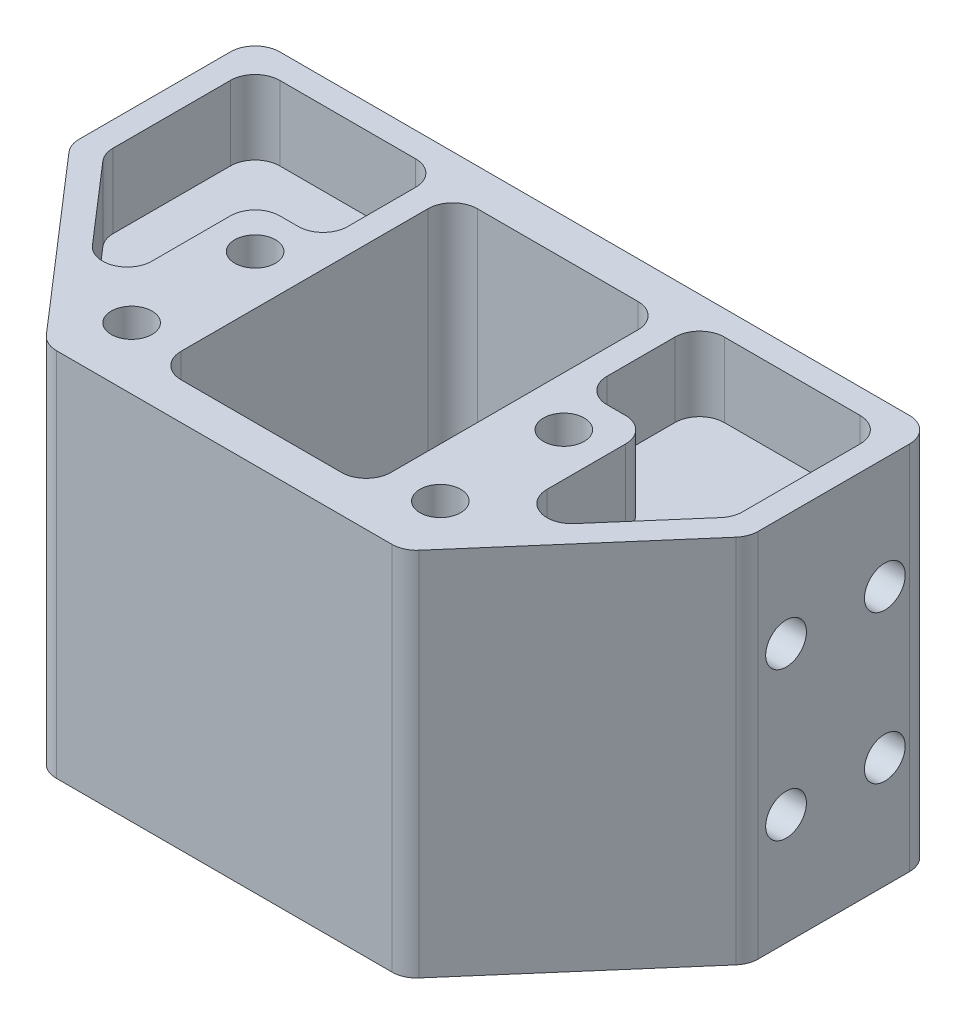
SolidWorks part; units mm, degrees
material "6061 合金"
ref_plane "前视基准面" through (0, 0, 0) normal (0, 0, 1) x (1, 0, 0)
ref_plane "上视基准面" through (0, 0, 0) normal (0, 1, 0) x (1, 0, 0)
ref_plane "右视基准面" through (0, 0, 0) normal (1, 0, 0) x (0, 0, -1)
other "Configuration Table"
sketch "草图1" plane through (0, 0, 0) normal (0, 0, 1) x (1, 0, 0)
  line L1 (-27.5, 15) -> (27.5, 15)
  line L2 (-27.5, 15) -> (-27.5, -15)
  line L3 (-27.5, -15) -> (27.5, -15)
  line L4 (27.5, 15) -> (27.5, -15)
  line L5 (-27.5, 15) -> (27.5, -15) construction
  line L6 (-27.5, -15) -> (27.5, 15) construction
  point P0 (0, 0)
  dimension "D1" = 55
  dimension "D2" = 30
extrude "凸台-拉伸1" add sketch "草图1" along normal blind 30
sketch "草图2" plane through (0, 15, 0) normal (0, 1, 0) x (1, 0, 0)
  line L0 (27.5, -30) -> (-27.5, -30) construction
  line L1 (-8.5, -3) -> (8.5, -3)
  line L2 (-8.5, -3) -> (-8.5, -27)
  line L3 (-8.5, -27) -> (8.5, -27)
  line L4 (8.5, -3) -> (8.5, -27)
  line L5 (-8.5, -3) -> (8.5, -27) construction
  line L6 (-8.5, -27) -> (8.5, -3) construction
  line L7 (27.5, 0) -> (-27.5, 0) construction
  line L9 (-12.5, -15) -> (12.5, -15) construction
  line L10 (-12.5, -15) -> (-12.5, -25) construction
  line L11 (-12.5, -25) -> (12.5, -25) construction
  line L12 (12.5, -15) -> (12.5, -25) construction
  line L13 (-12.5, -15) -> (12.5, -25) construction
  line L14 (-12.5, -25) -> (12.5, -15) construction
  circle A0 centre (12.5, -25) radius 1.65
  circle A1 centre (-12.5, -25) radius 1.65
  circle A2 centre (-12.5, -15) radius 1.65
  circle A3 centre (12.5, -15) radius 1.65
  point P0 (0, -15)
  point P10 (0, -20)
  dimension "D9" = 3.3
  dimension "D1" = 17
  dimension "D2" = 3
  dimension "D3" = 3
  dimension "D4" = 5
  dimension "D7" = 25
  dimension "D8" = 10
  dimension "D5" = 2
  dimension "D6" = 2
extrude "切除-拉伸1" cut sketch "草图2" against normal blind 40
sketch "草图7" plane through (0, 15, 0) normal (0, 1, 0) x (1, 0, 0)
  line L0 (27.5, -15) -> (27.5, -30)
  line L1 (27.5, -30) -> (27.5, 0) construction
  line L2 (27.5, -30) -> (14.5, -30)
  line L3 (27.5, -30) -> (-27.5, -30) construction
  line L4 (14.5, -30) -> (27.5, -15)
  line L5 (-14.5, -30) -> (-27.5, -30)
  line L6 (-27.5, -30) -> (-27.5, -15)
  line L7 (-27.5, -30) -> (-27.5, 0) construction
  line L8 (-27.5, -15) -> (-14.5, -30)
  dimension "D1" = 13
  dimension "D2" = 15
  dimension "D3" = 13
extrude "切除-拉伸3" cut sketch "草图7" against normal blind 40
sketch "草图8" plane through (0, 15, 0) normal (0, 1, 0) x (1, 0, 0)
  line L6 (-16, -25.2155) -> (-16, -11.5)
  line L7 (-16, -11.5) -> (-10.5, -11.5)
  line L8 (-10.5, -11.5) -> (-10.5, -2)
  line L9 (16, -25.2155) -> (16, -11.5)
  line L10 (16, -11.5) -> (10.5, -11.5)
  line L11 (10.5, -11.5) -> (10.5, -2)
  line L12 (-13.5867, -28) -> (13.5867, -28)
  line L13 (13.5867, -28) -> (25.5, -14.2539)
  line L14 (25.5, -14.2539) -> (25.5, -2)
  line L15 (25.5, -2) -> (-25.5, -2)
  line L16 (-25.5, -2) -> (-25.5, -14.2539)
  line L17 (-25.5, -14.2539) -> (-13.5867, -28)
  line L19 (16, -25.2155) -> (25.5, -14.2539)
  line L20 (25.5, -14.2539) -> (25.5, -2)
  line L21 (25.5, -2) -> (10.5, -2)
  line L22 (-25.5, -2) -> (-25.5, -14.2539)
  line L23 (-25.5, -14.2539) -> (-16, -25.2155)
  line L24 (-10.5, -2) -> (-25.5, -2)
  line L25 (-8.5, -3) -> (-8.5, -27) construction
  line L26 (8.5, -27) -> (8.5, -3) construction
  circle A0 centre (-12.5, -15) radius 1.65 construction
  circle A1 centre (12.5, -15) radius 1.65 construction
  dimension "D2" = 3.5
  dimension "D6" = 3.5
  dimension "D3" = 3.5
  dimension "D4" = 2
  dimension "D5" = 2
  dimension "D7" = 3.5
  dimension "D1" = 2
extrude "切除-拉伸4" cut sketch "草图8" against normal blind 6
sketch "草图9" plane through (0, -15, 0) normal (0, -1, 0) x (1, 0, 0)
  line L6 (-16, 25.2155) -> (-16, 11.5)
  line L7 (-16, 11.5) -> (-10.5, 11.5)
  line L8 (-10.5, 11.5) -> (-10.5, 2)
  line L10 (16.6684, 24.4443) -> (16, 11.5)
  line L11 (16, 11.5) -> (10.5, 11.5)
  line L12 (25.5, 2) -> (25.5, 14.2539)
  line L13 (25.5, 14.2539) -> (13.5867, 28)
  line L14 (13.5867, 28) -> (-13.5867, 28)
  line L15 (-13.5867, 28) -> (-25.5, 14.2539)
  line L16 (-25.5, 14.2539) -> (-25.5, 2)
  line L17 (-25.5, 2) -> (25.5, 2)
  line L18 (25.5, 2) -> (25.5, 14.2539)
  line L19 (25.5, 14.2539) -> (16.6684, 24.4443)
  line L21 (-16, 25.2155) -> (-25.5, 14.2539)
  line L22 (-25.5, 14.2539) -> (-25.5, 2)
  line L23 (-25.5, 2) -> (-10.5, 2)
  line L24 (10.5, 11.5) -> (10.5, 2)
  line L25 (-8.5, 3) -> (-8.5, 27) construction
  line L26 (10.5, 2) -> (25.5, 2)
  circle A0 centre (-12.5, 15) radius 1.65 construction
  dimension "D2" = 2
  dimension "D3" = 3.5
  dimension "D4" = 3.5
  dimension "D1" = 2
extrude "切除-拉伸5" cut sketch "草图9" against normal blind 6
fillet "圆角1" radius 2 16 edges at (-8.5, 0, 27) (-8.5, 0, 3) (8.5, 0, 3) (8.5, 0, 27) (25.5, -12, 14.2539) (16.6684, -12, 24.4443) (16, -12, 11.5) (10.5, -12, 11.5) (10.5, -12, 2) (25.5, -12, 2) (-25.5, -12, 2) (-10.5, -12, 2) (-10.5, -12, 11.5) (-16, -12, 11.5) (-25.5, -12, 14.2539) (-16, -12, 25.2155)
fillet "圆角2" radius 2 12 edges at (10.5, 12, 2) (10.5, 12, 11.5) (16, 12, 11.5) (16, 12, 25.2155) (25.5, 12, 14.2539) (-16, 12, 11.5) (-10.5, 12, 11.5) (-10.5, 12, 2) (-25.5, 12, 2) (-25.5, 12, 14.2539) (-16, 12, 25.2155) (25.5, 12, 2)
fillet "圆角3" radius 2 6 edges at (-27.5, 0, 0) (-27.5, 0, 15) (-14.5, 0, 30) (14.5, 0, 30) (27.5, 0, 15) (27.5, 0, 0)
sketch "草图10" plane through (-27.5, 0, 0) normal (-1, 0, 0) x (0, 0, 1)
  line L0 (0, -15) -> (0, 15) construction
  line L1 (4, 6) -> (12, 6) construction
  line L2 (4, 6) -> (4, -6) construction
  line L3 (4, -6) -> (12, -6) construction
  line L4 (12, 6) -> (12, -6) construction
  line L5 (4, 6) -> (12, -6) construction
  line L6 (4, -6) -> (12, 6) construction
  circle A0 centre (12, -6) radius 1.65
  circle A1 centre (4, -6) radius 1.65
  circle A2 centre (4, 6) radius 1.65
  circle A3 centre (12, 6) radius 1.65
  point P0 (8, 0)
  dimension "D6" = 3.3
  dimension "D1" = 8
  dimension "D2" = 8
  dimension "D3" = 12
  dimension "D5" = 2
  dimension "D4" = 2
extrude "切除-拉伸7" cut sketch "草图10" against normal blind 8
sketch "草图11" plane through (27.5, 0, 0) normal (1, 0, 0) x (0, 0, -1)
  line L0 (0, 15) -> (0, -15) construction
  line L1 (-12, 6) -> (-4, 6) construction
  line L2 (-12, 6) -> (-12, -6) construction
  line L3 (-12, -6) -> (-4, -6) construction
  line L4 (-4, 6) -> (-4, -6) construction
  line L5 (-12, 6) -> (-4, -6) construction
  line L6 (-12, -6) -> (-4, 6) construction
  circle A0 centre (-12, 6) radius 1.65
  circle A1 centre (-4, 6) radius 1.65
  circle A2 centre (-4, -6) radius 1.65
  circle A3 centre (-12, -6) radius 1.65
  point P0 (-8, 0)
  dimension "D6" = 3.3
  dimension "D1" = 8
  dimension "D3" = 12
  dimension "D4" = 8
  dimension "D5" = 2
  dimension "D2" = 2
extrude "切除-拉伸8" cut sketch "草图11" against normal blind 8
